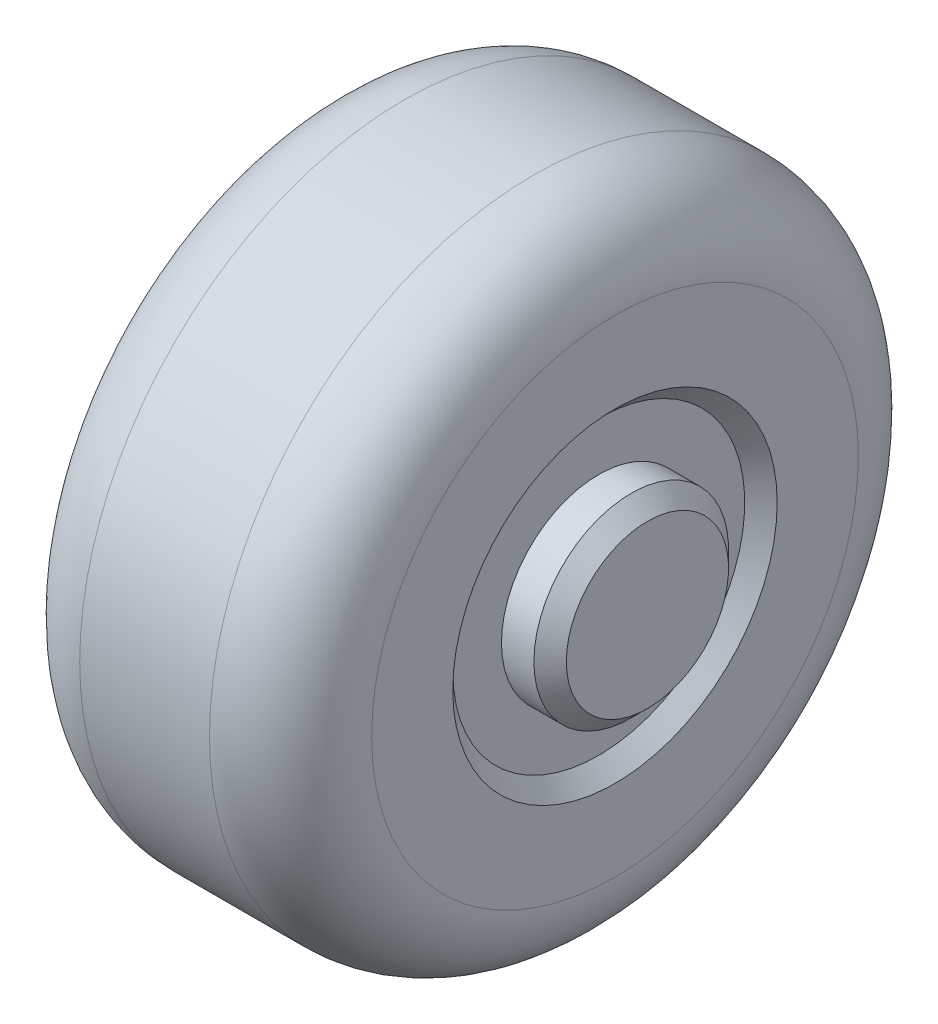
SolidWorks part; units mm, degrees
ref_plane "Front Plane" through (0, 0, 0) normal (0, 0, 1) x (1, 0, 0)
ref_plane "Top Plane" through (0, 0, 0) normal (0, 1, 0) x (1, 0, 0)
ref_plane "Right Plane" through (0, 0, 0) normal (1, 0, 0) x (0, 0, -1)
ref_plane "Plane1" through (0, 0, 0) normal (0, 0, 1) x (1, 0, 0)
sketch "Sketch1" plane through (0, 0, 0) normal (0, 0, 1) x (1, 0, 0)
  line L0 (-11, 0) -> (-11, 5)
  line L1 (-11, 5) -> (-10, 6)
  line L2 (-10, 6) -> (-8, 6)
  line L3 (-8, 6) -> (-8, 9)
  line L4 (-8, 9) -> (-9, 10)
  line L5 (-9, 10) -> (-9, 15)
  line L6 (-4, 20) -> (4, 20)
  line L7 (9, 15) -> (9, 10)
  line L8 (9, 10) -> (8, 9)
  line L9 (8, 9) -> (8, 6)
  line L10 (8, 6) -> (10, 6)
  line L11 (10, 6) -> (11, 5)
  line L12 (11, 5) -> (11, 0)
  line L13 (11, 0) -> (-11, 0)
  line L14 (11, 0) -> (-11, 0) construction
  arc A0 (-9, 15) -> (-4, 20) centre (-4, 15) cw
  arc A1 (4, 20) -> (9, 15) centre (4, 15) cw
revolve "Revolve1" add sketch "Sketch1" angle 360 about L14
